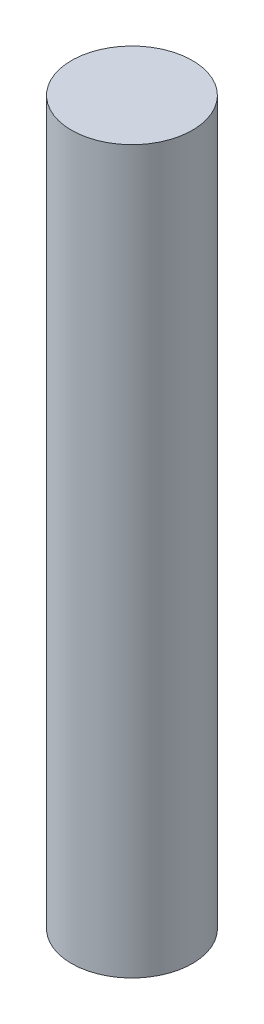
SolidWorks part; units mm, degrees
ref_plane "Front Plane" through (0, 0, 0) normal (0, 0, 1) x (1, 0, 0)
ref_plane "Top Plane" through (0, 0, 0) normal (0, 1, 0) x (1, 0, 0)
ref_plane "Right Plane" through (0, 0, 0) normal (1, 0, 0) x (0, 0, -1)
sketch "Sketch1" plane through (0, 0, 0) normal (0, 1, 0) x (1, 0, 0)
  circle A0 centre (0, 0) radius 1.675
  dimension "D1" = 3.35
extrude "Boss-Extrude1" add sketch "Sketch1" along normal blind 20
